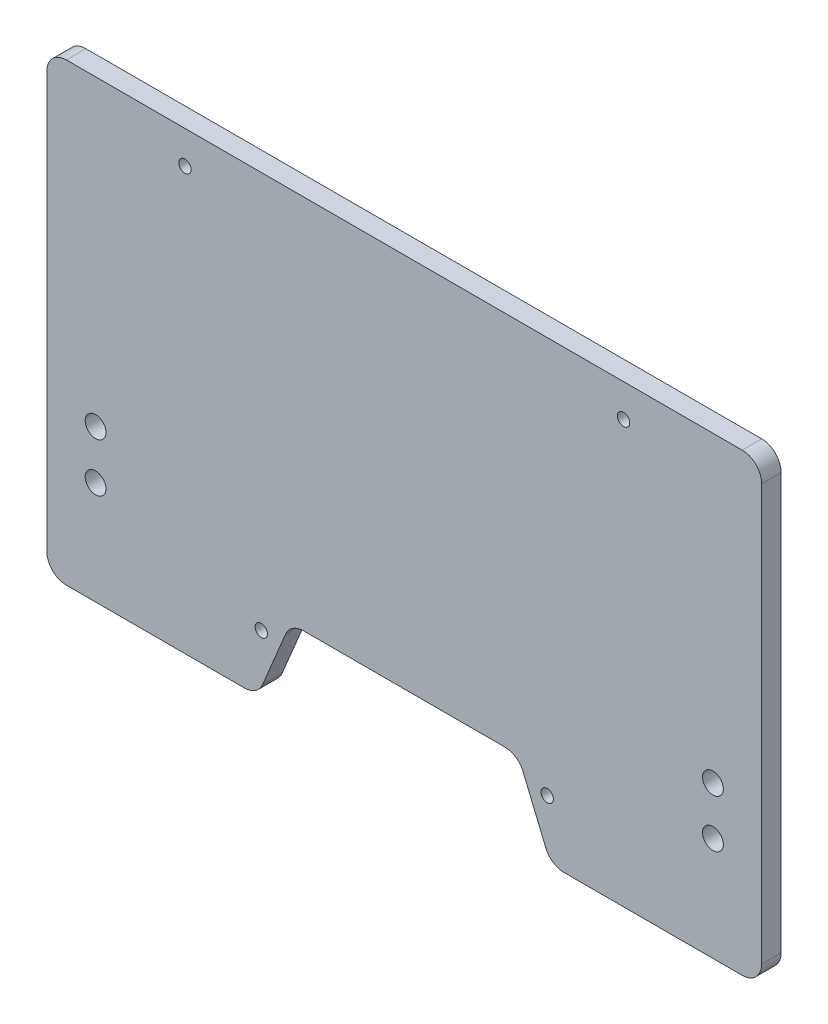
SolidWorks part; units mm, degrees
ref_plane "前视基准面" through (0, 0, 0) normal (0, 0, 1) x (1, 0, 0)
ref_plane "上视基准面" through (0, 0, 0) normal (0, 1, 0) x (1, 0, 0)
ref_plane "右视基准面" through (0, 0, 0) normal (1, 0, 0) x (0, 0, -1)
sketch "草图1" plane through (0, 0, 0) normal (0, 0, 1) x (1, 0, 0)
  line L0 (32, 23.2799) -> (63, 23.2799)
  line L1 (-4.5, 81.1154) -> (99.5, 81.1154)
  line L2 (-7.5, 78.1154) -> (-7.5, 14.1154)
  line L3 (-4.5, 11.1154) -> (22.9315, 11.1154)
  line L4 (102.5, 78.1154) -> (102.5, 14.1154)
  line L5 (90.5, 11.1154) -> (99.5, 11.1154) construction
  line L6 (102.5, 14.1154) -> (102.5, 28.65) construction
  line L7 (28.2692, 19.1261) -> (29.2308, 21.4338) construction
  line L9 (65.7692, 21.4338) -> (66.7308, 19.1261) construction
  line L10 (65.7692, 21.4338) -> (66.7308, 19.1261)
  line L11 (28.2692, 19.1261) -> (25.7007, 12.9616)
  line L12 (28.2692, 19.1261) -> (29.2308, 21.4338)
  line L14 (66.7308, 19.1261) -> (69.2993, 12.9616)
  line L15 (72.0685, 11.1154) -> (99.5, 11.1154)
  arc A0 (99.5, 81.1154) -> (102.5, 78.1154) centre (99.5, 78.1154) cw
  arc A1 (-4.5, 81.1154) -> (-7.5, 78.1154) centre (-4.5, 78.1154) ccw
  arc A2 (-7.5, 14.1154) -> (-4.5, 11.1154) centre (-4.5, 14.1154) ccw
  arc A3 (99.5, 11.1154) -> (102.5, 14.1154) centre (99.5, 14.1154) ccw
  circle A4 centre (0, 34.5) radius 1.6
  arc A5 (32, 23.2799) -> (29.2308, 21.4338) centre (32, 20.2799) ccw construction
  arc A6 (65.7692, 21.4338) -> (63, 23.2799) centre (63, 20.2799) ccw construction
  circle A7 centre (0, 27) radius 1.6
  arc A8 (69.2993, 12.9616) -> (72.0685, 11.1154) centre (72.0685, 14.1154) ccw
  arc A9 (25.7007, 12.9616) -> (22.9315, 11.1154) centre (22.9315, 14.1154) cw
  arc A10 (65.7692, 21.4338) -> (63, 23.2799) centre (63, 20.2799) ccw
  arc A11 (32, 23.2799) -> (29.2308, 21.4338) centre (32, 20.2799) ccw
  circle A12 centre (95, 34.5) radius 1.6
  circle A13 centre (95, 27.1) radius 1.6
  circle A14 centre (13.75, 76.0799) radius 0.95
  circle A15 centre (81.25, 76.0799) radius 0.95
  circle A16 centre (69.5, 20.0799) radius 0.95
  circle A17 centre (25.5, 20.0799) radius 0.95
  point P21 (70.0685, 11.1154)
  dimension "D2" = 3
  dimension "D3" = 3
  dimension "D4" = 3.2
  dimension "D5" = 1.9
  dimension "D1" = 70
extrude "凸台-拉伸1" add sketch "草图1" along normal blind 3
